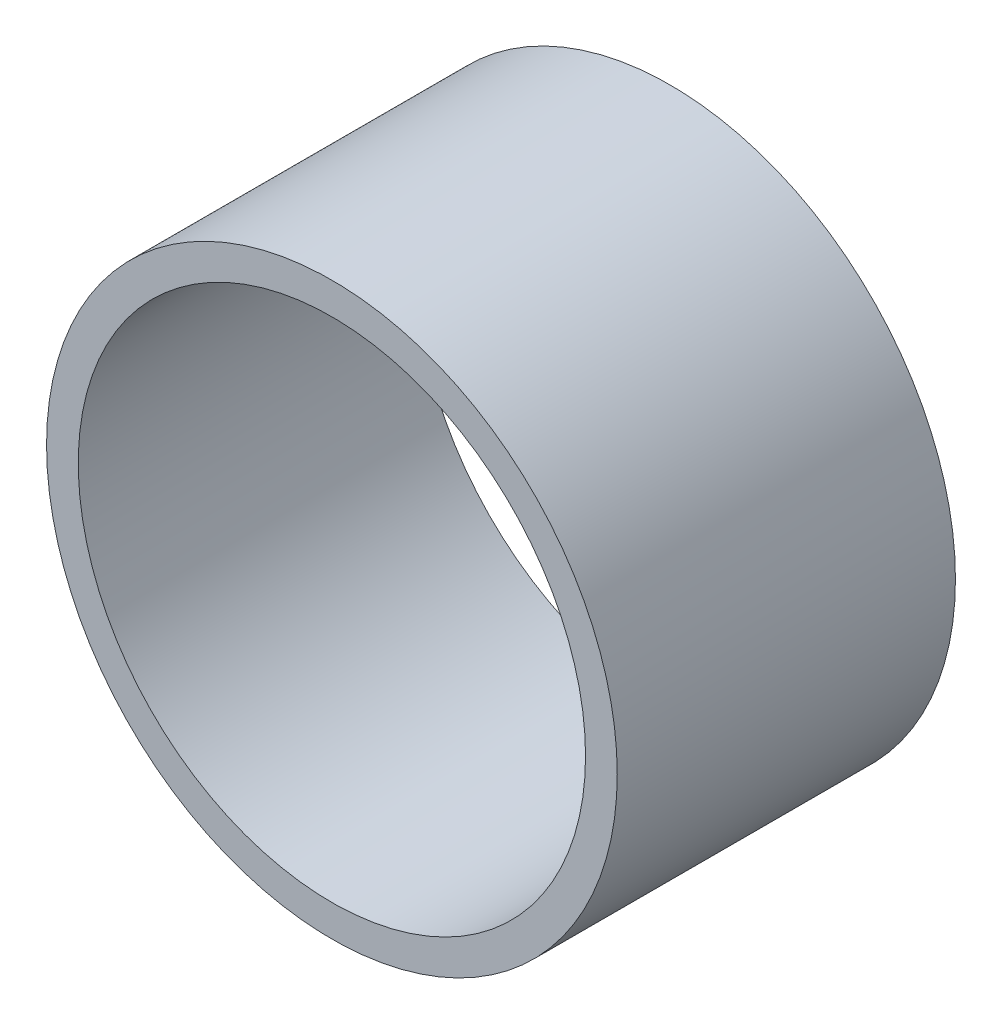
SolidWorks part; units mm, degrees
ref_plane "Front Plane" through (0, 0, 0) normal (0, 0, 1) x (1, 0, 0)
ref_plane "Top Plane" through (0, 0, 0) normal (0, 1, 0) x (1, 0, 0)
ref_plane "Right Plane" through (0, 0, 0) normal (1, 0, 0) x (0, 0, -1)
sketch "Sketch2" plane through (0, 0, 0) normal (0, 0, 1) x (1, 0, 0)
  circle A0 centre (0, 0) radius 67.5
  dimension "D1" = 135
extrude "Boss-Extrude1" add sketch "Sketch2" along normal mid plane 80
sketch "Sketch3" plane through (0, 0, 40) normal (0, 0, 1) x (1, 0, 0)
  circle A0 centre (0, 0) radius 60
  dimension "D1" = 120
extrude "Cut-Extrude1" cut sketch "Sketch3" against normal through all contours A0
